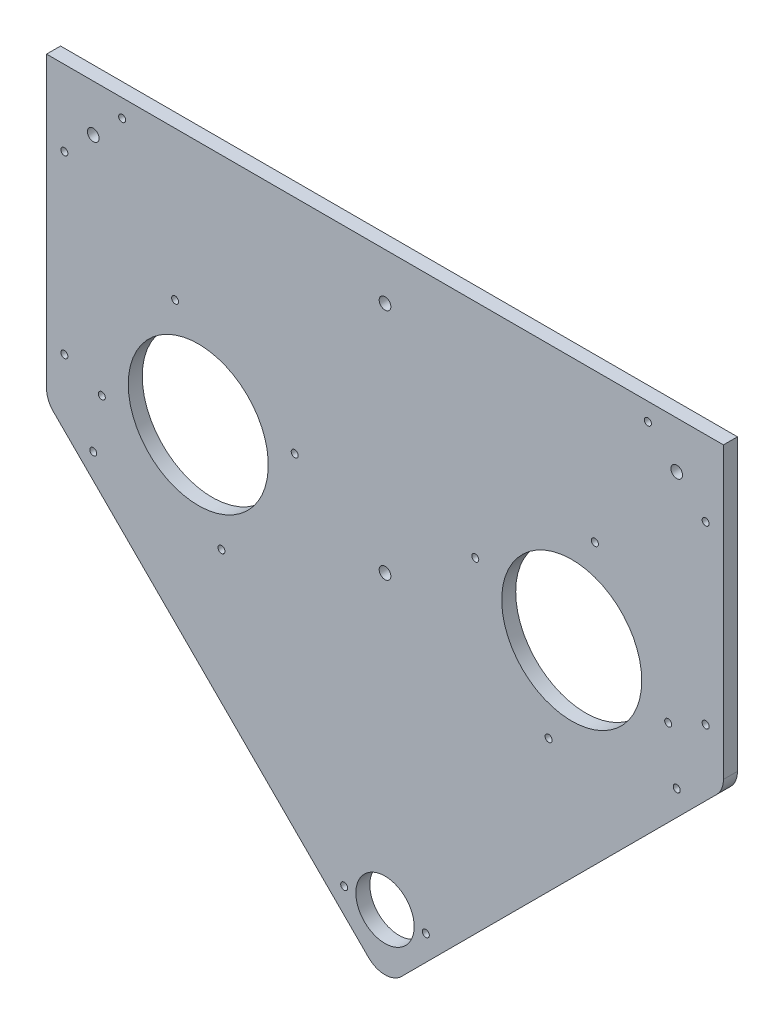
SolidWorks part; units mm, degrees
ref_plane "Front Plane" through (0, 0, 0) normal (0, 0, 1) x (1, 0, 0)
ref_plane "Top Plane" through (0, 0, 0) normal (0, 1, 0) x (1, 0, 0)
ref_plane "Right Plane" through (0, 0, 0) normal (1, 0, 0) x (0, 0, -1)
sketch "Sketch1" plane through (0, 0, 0) normal (0, 0, 1) x (1, 0, 0)
  line L0 (-125, 100) -> (125, 100) construction
  line L1 (-125, 0) -> (125, 0) construction
  line L2 (-137.3744, 87.6256) -> (-125, 100) construction
  line L3 (0, -125) -> (-125, 0) construction
  line L4 (0, -125) -> (-17.5, -125) construction
  line L5 (-125, -17.5) -> (-125, 0) construction
  line L6 (0, -125) -> (0, 100) construction
  line L7 (-145, 120) -> (145, 120)
  line L8 (145, 120) -> (145, -8.2843)
  line L9 (145, -8.2843) -> (0, -153.2843)
  line L10 (0, -153.2843) -> (-145, -8.2843)
  line L11 (-145, -8.2843) -> (-145, 120)
  circle A0 centre (-125, 100) radius 12.5 construction
  circle A1 centre (125, 100) radius 12.5 construction
  circle A4 centre (0, -125) radius 12.5
  circle A5 centre (-137.3744, 87.6256) radius 1.5
  circle A6 centre (-112.6256, 112.3744) radius 1.5
  circle A7 centre (-137.3744, 12.3744) radius 1.5
  circle A8 centre (-125, -17.5) radius 1.5
  circle A9 centre (-17.5, -125) radius 1.5
  circle A10 centre (-125, 0) radius 12.5 construction
  circle A11 centre (125, 0) radius 12.5 construction
  circle A12 centre (-125, 0) radius 17.5 construction
  circle A13 centre (-125, 100) radius 17.5 construction
  circle A14 centre (0, -125) radius 17.5 construction
  circle A15 centre (17.5, -125) radius 1.5
  circle A16 centre (125, -17.5) radius 1.5
  circle A17 centre (137.3744, 12.3744) radius 1.5
  circle A18 centre (137.3744, 87.6256) radius 1.5
  circle A19 centre (112.6256, 112.3744) radius 1.5
  circle A20 centre (0, 100) radius 2.5
  circle A21 centre (-125, 100) radius 2.5
  circle A22 centre (125, 100) radius 2.5
  circle A23 centre (0, 0) radius 2.5
  point P12 (0, 100)
  point P45 (0, 120)
  dimension "D1" = 25
  dimension "D5" = 3
  dimension "D2" = 5
  dimension "D17" = 5
  dimension "D4" = 100
  dimension "D6" = 5
  dimension "D7" = 135
  dimension "D8" = 45
  dimension "D9" = 250
  dimension "D10" = 45
  dimension "D11" = 20
  dimension "D12" = 20
  dimension "D13" = 20
  dimension "D14" = 20
  dimension "D15" = 20
  dimension "D3" = 125
  dimension "D16" = 125
extrude "Boss-Extrude1" add sketch "Sketch1" along normal blind 6
fillet "Fillet1" radius 10 3 edges at (-145, -8.2843, 3) (145, -8.2843, 3) (0, -153.2843, 3)
sketch "Sketch2" plane through (0, 0, 6) normal (0, 0, 1) x (1, 0, 0)
  line L0 (121.326, 5.0796) -> (38.674, 24.9204) construction
  line L1 (70.0796, -26.326) -> (89.9204, 56.326) construction
  line L2 (0, 0) -> (0, 100) construction
  line L3 (145, 120) -> (-145, 120) construction
  line L4 (-145, 120) -> (-145, -4.1421) construction
  line L5 (-80, 15) -> (80, 15) construction
  circle A0 centre (80, 15) radius 42.5 construction
  circle A1 centre (38.674, 24.9204) radius 1.5
  circle A2 centre (89.9204, 56.326) radius 1.5
  circle A3 centre (121.326, 5.0796) radius 1.5
  circle A4 centre (70.0796, -26.326) radius 1.5
  circle A5 centre (80, 15) radius 30
  circle A6 centre (-38.674, 24.9204) radius 1.5
  circle A7 centre (-89.9204, 56.326) radius 1.5
  circle A8 centre (-70.0796, -26.326) radius 1.5
  circle A9 centre (-121.326, 5.0796) radius 1.5
  circle A10 centre (-80, 15) radius 42.5 construction
  circle A11 centre (-80, 15) radius 30
  circle A12 centre (-80, 15) radius 47.5 construction
  circle A13 centre (-137.3744, 12.3744) radius 3 construction
  circle A14 centre (-125, -17.5) radius 3 construction
  point P6 (80, 15)
  point P27 (-80, 15)
  dimension "D1" = 85
  dimension "D2" = 3
  dimension "D3" = 60
  dimension "D4" = 95
  dimension "D5" = 6
  dimension "D6" = 105
  dimension "D7" = 65
extrude "Cut-Extrude1" cut sketch "Sketch2" against normal blind 10
equation "\"D1@Sketch1\" = \"cf_tube_outer_diameter\""
equation "\"D9@Sketch1\"= \"mid_plate_horizontal_spacing\""
equation "\"mid_plate_mid_to_top\" = 100mm"
equation "\"mid_plate_mid_to_bottom\" = 125mm"
equation "\"mid_plate_horizontal_spacing\" = 250mm"
equation "\"cf_tube_outer_diameter\" = 25mm"
equation "\"D4@Sketch1\"=\"mid_plate_mid_to_top\""
equation "\"D3@Sketch1\"=\"mid_plate_mid_to_bottom\""
